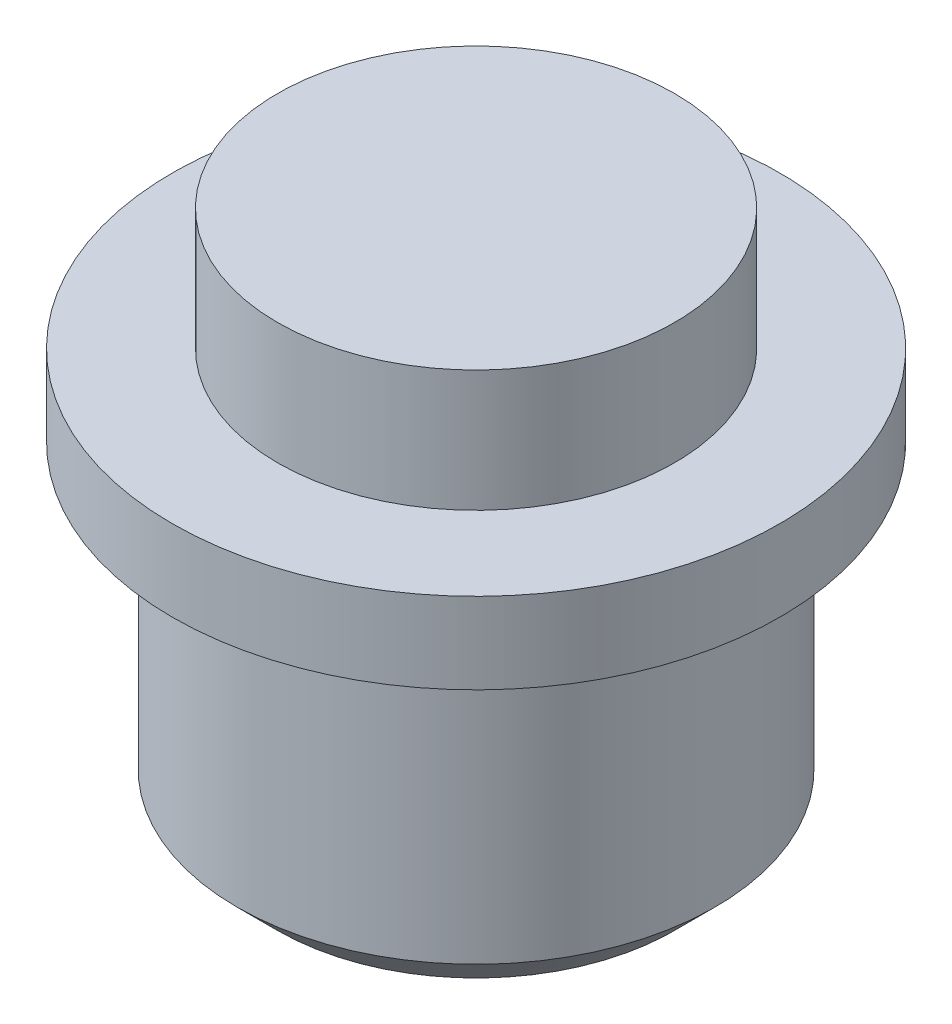
SolidWorks part; units mm, degrees
ref_plane "Front Plane" through (0, 0, 0) normal (0, 0, 1) x (1, 0, 0)
ref_plane "Top Plane" through (0, 0, 0) normal (0, 1, 0) x (1, 0, 0)
ref_plane "Right Plane" through (0, 0, 0) normal (1, 0, 0) x (0, 0, -1)
sketch "Sketch1" plane through (0, 0, 0) normal (0, 1, 0) x (1, 0, 0)
  circle A0 centre (0, 0) radius 4.9
  dimension "D1" = 9.8
extrude "Boss-Extrude1" add sketch "Sketch1" along normal blind 5
ref_plane "Plane4" through (0, 2, 0) normal (0, 1, 0) x (1, 0, 0)
sketch "Sketch2" plane through (0, 2, 0) normal (0, 1, 0) x (1, 0, 0)
  circle A0 centre (0, 0) radius 7.5
  dimension "D1" = 15
extrude "Boss-Extrude2" add sketch "Sketch2" against normal blind 2
sketch "Sketch3" plane through (0, 0, 0) normal (0, 1, 0) x (1, 0, 0)
  circle A0 centre (0, 0) radius 5.9
  dimension "D1" = 11.8
extrude "Boss-Extrude3" add sketch "Sketch3" against normal blind 8
chamfer "Chamfer1" distance 1 angle 45 1 edges at (0, -8, 5.9)
equation "\"5mmm\"=0.0625"
